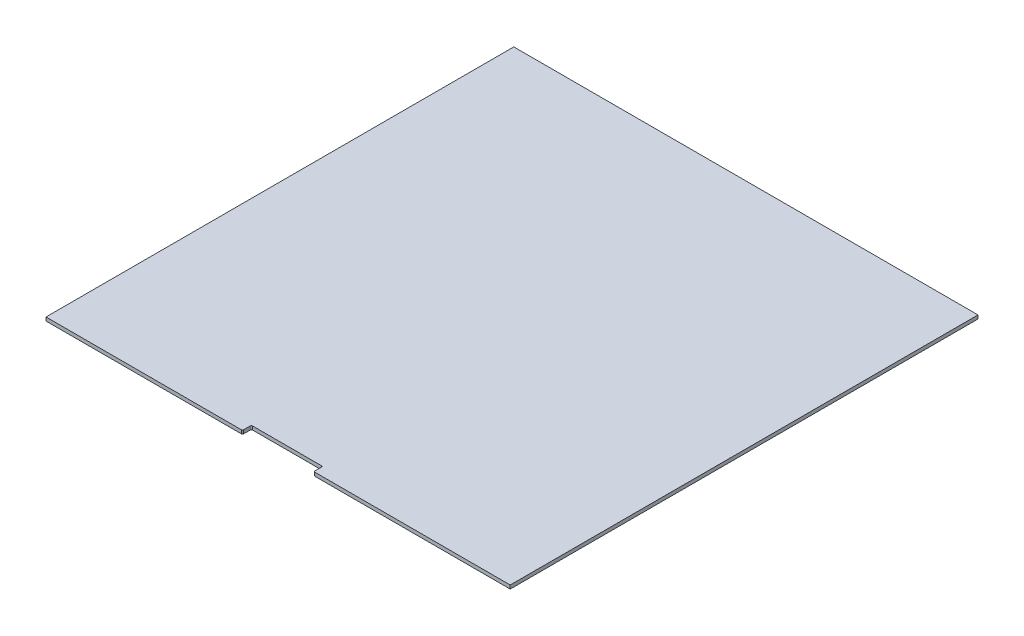
SolidWorks part; units mm, degrees
ref_plane "前基準面" through (0, 0, 0) normal (0, 0, 1) x (1, 0, 0)
ref_plane "上基準面" through (0, 0, 0) normal (0, 1, 0) x (1, 0, 0)
ref_plane "右基準面" through (0, 0, 0) normal (1, 0, 0) x (0, 0, -1)
sketch "草圖1" plane through (0, 0, 0) normal (0, 1, 0) x (1, 0, 0)
  line L1 (-195.5, 197) -> (195.5, 197)
  line L2 (-195.5, 197) -> (-195.5, -197)
  line L3 (-195.5, -197) -> (195.5, -197)
  line L4 (195.5, 197) -> (195.5, -197)
  line L5 (-195.5, 197) -> (195.5, -197) construction
  line L6 (-195.5, -197) -> (195.5, 197) construction
  point P0 (0, 0)
  dimension "D1" = 394
  dimension "D2" = 391
extrude "填料-伸長1" add sketch "草圖1" along normal blind 3
sketch "草圖2" plane through (0, 3, 0) normal (0, 1, 0) x (1, 0, 0)
  line L0 (-195.5, -197) -> (195.5, -197) construction
  line L1 (-30, -197) -> (30, -197)
  line L2 (-30, -197) -> (-30, -189.5)
  line L3 (-30, -189.5) -> (30, -189.5)
  line L4 (30, -197) -> (30, -189.5)
  line L5 (0, -1.65) -> (0, 1.65) construction
  dimension "D1" = 7.5
  dimension "D2" = 60
  dimension "D3" = 30
extrude "除料-伸長1" cut sketch "草圖2" against normal through all
fillet "圓角1" radius 1 4 edges at (30, 1.5, 197) (30, 1.5, 189.5) (-30, 1.5, 189.5) (-30, 1.5, 197)
